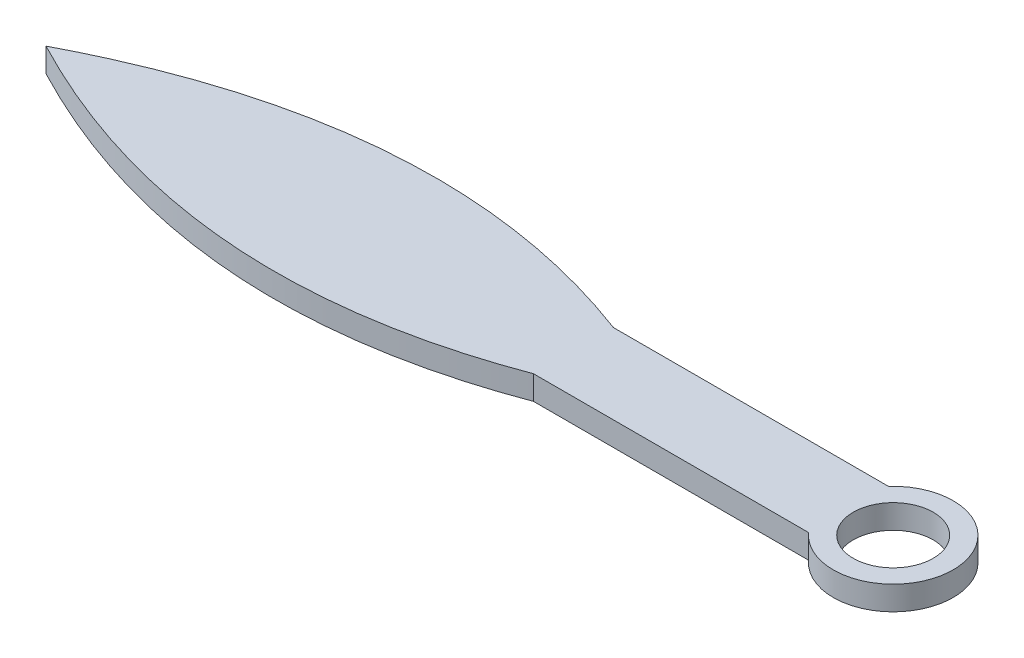
SolidWorks part; units mm, degrees
ref_plane "Front Plane" through (0, 0, 0) normal (0, 0, 1) x (1, 0, 0)
ref_plane "Top Plane" through (0, 0, 0) normal (0, 1, 0) x (1, 0, 0)
ref_plane "Right Plane" through (0, 0, 0) normal (1, 0, 0) x (0, 0, -1)
sketch "Sketch1" plane through (0, 0, 0) normal (0, 1, 0) x (1, 0, 0)
  line L0 (-269.1843, 0) -> (-101.6, 0) construction
  line L1 (-14.199, 12.7) -> (-101.6, 12.7)
  line L3 (-14.199, -12.7) -> (-101.6, -12.7)
  line L5 (0, 12.7) -> (-101.6, -12.7) construction
  line L6 (0, -12.7) -> (-101.6, 12.7) construction
  circle A0 centre (0, 0) radius 12.7
  arc A1 (-14.199, -12.7) -> (-14.199, 12.7) centre (0, 0) ccw
  spline S0 degree 2 poles (-101.6, 12.7) (-184.8833, 44.0147) (-269.1843, 0) knots 0 0 0 1 1 1
  spline S1 degree 2 poles (-101.6, -12.7) (-184.8833, -44.0147) (-269.1843, 0) knots 0 0 0 1 1 1
  point P4 (-50.8, 0)
  dimension "D2" = 38.1
  dimension "D3" = 25.4
  dimension "D1" = 101.6
  dimension "D4" = 25.4
extrude "Boss-Extrude1" add sketch "Sketch1" along normal blind 7.62
